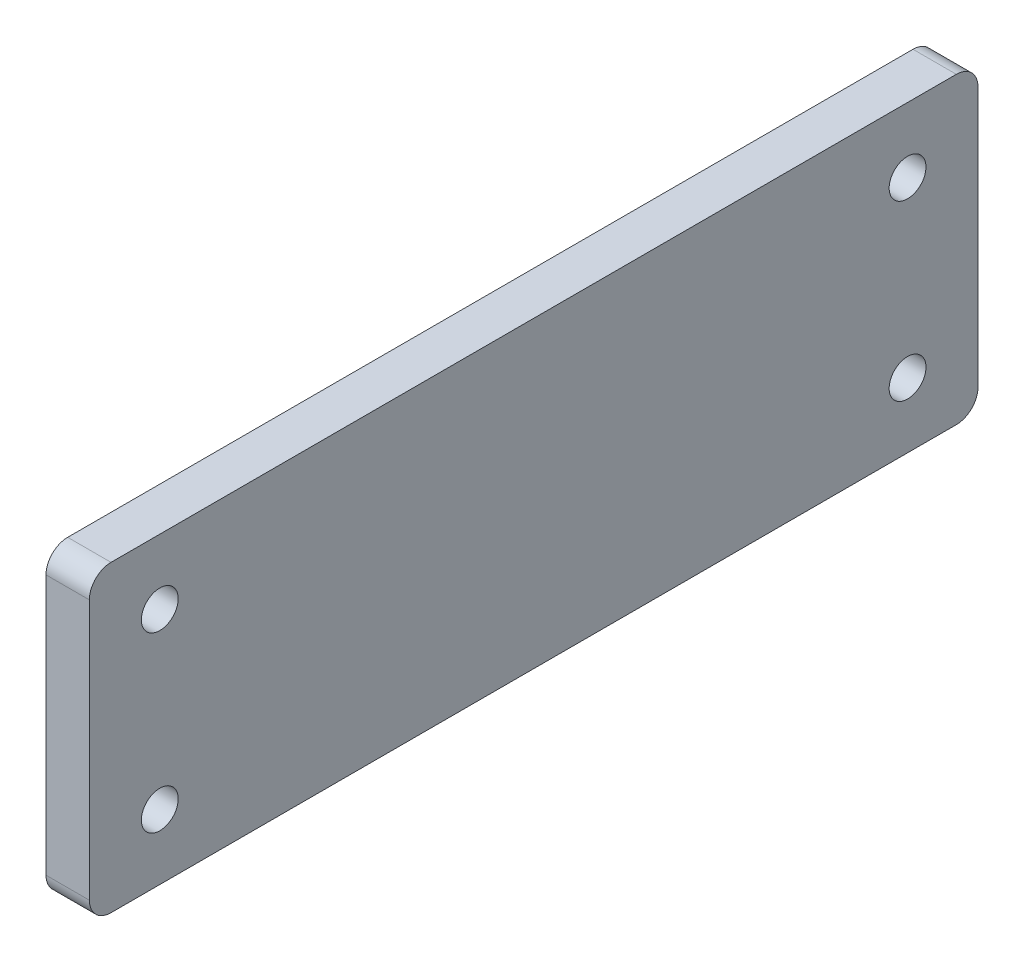
SolidWorks part; units mm, degrees
ref_plane "前视基准面" through (0, 0, 0) normal (0, 0, 1) x (1, 0, 0)
ref_plane "上视基准面" through (0, 0, 0) normal (0, 1, 0) x (1, 0, 0)
ref_plane "右视基准面" through (0, 0, 0) normal (1, 0, 0) x (0, 0, -1)
sketch "草图1" plane through (0, 0, 0) normal (1, 0, 0) x (0, 0, -1)
  line L0 (0, 31.1637) -> (0, 0) construction
  line L1 (-19.5, 7) -> (19.5, 7)
  line L2 (-20.5, 6) -> (-20.5, -6)
  line L3 (-19.5, -7) -> (19.5, -7)
  line L4 (20.5, 6) -> (20.5, -6)
  line L5 (0, 0) -> (52.9879, 0) construction
  line L6 (-20.5, -6) -> (-20.5, 6) construction
  line L7 (20.5, 6) -> (20.5, -6) construction
  line L8 (15, -7) -> (19.5, -7) construction
  arc A0 (-20.5, -6) -> (-19.5, -7) centre (-19.5, -6) ccw
  arc A1 (-19.5, 7) -> (-20.5, 6) centre (-19.5, 6) ccw
  arc A2 (19.5, 7) -> (20.5, 6) centre (19.5, 6) cw
  arc A3 (19.5, -7) -> (20.5, -6) centre (19.5, -6) ccw
  circle A4 centre (-17.25, 4) radius 0.85
  circle A5 centre (-17.25, -4) radius 0.85
  circle A6 centre (17.25, -4) radius 0.85
  circle A7 centre (17.25, 4) radius 0.85
  dimension "D1" = 1
  dimension "D2" = 1.7
extrude "凸台-拉伸1" add sketch "草图1" along normal blind 2
